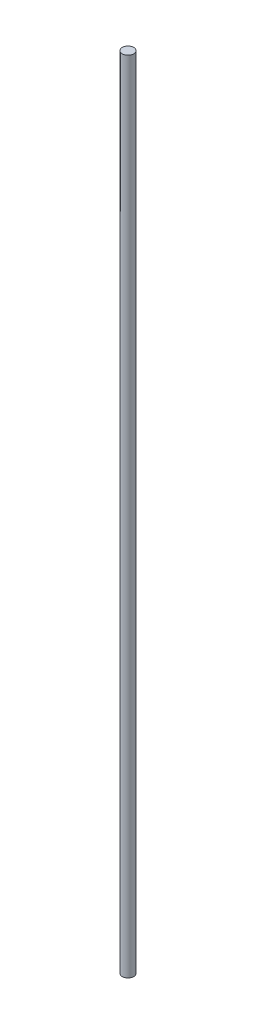
SolidWorks part; units mm, degrees
ref_plane "Front Plane" through (0, 0, 0) normal (0, 0, 1) x (1, 0, 0)
ref_plane "Top Plane" through (0, 0, 0) normal (0, 1, 0) x (1, 0, 0)
ref_plane "Right Plane" through (0, 0, 0) normal (1, 0, 0) x (0, 0, -1)
sketch "Sketch1" plane through (0, 0, 0) normal (0, 1, 0) x (1, 0, 0)
  circle A0 centre (0, 0) radius 1.5875
  dimension "D1" = 3.175
extrude "Boss-Extrude1" add sketch "Sketch1" along normal blind 224.0839
